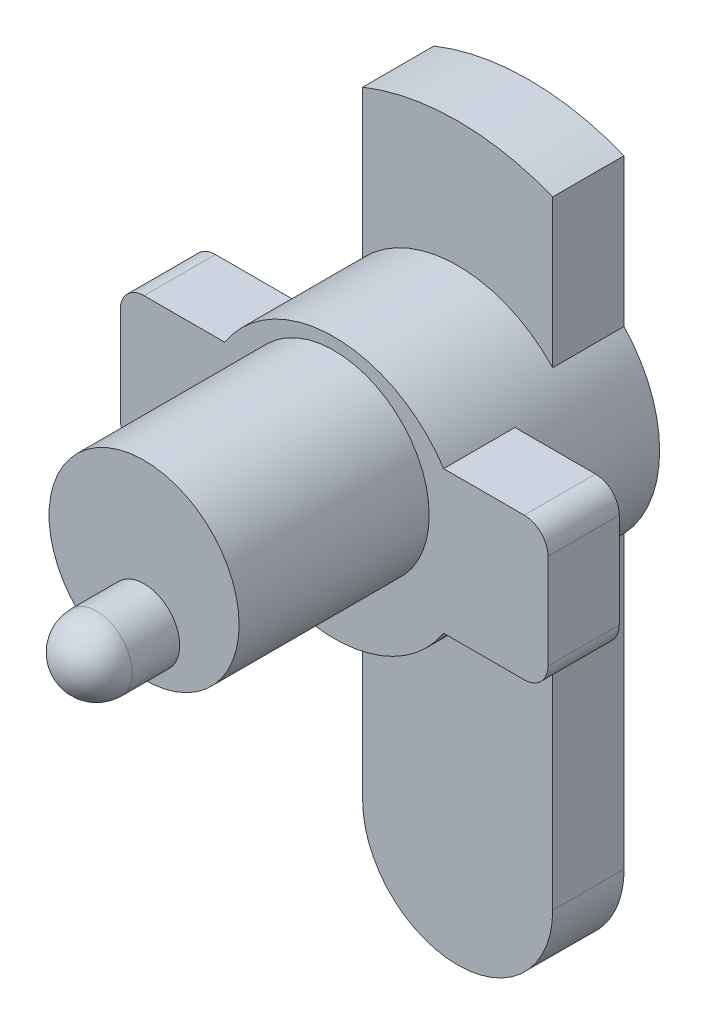
SolidWorks part; units mm, degrees
material "ABS PC"
ref_plane "Piano frontale" through (0, 0, 0) normal (0, 0, 1) x (1, 0, 0)
ref_plane "Piano superiore" through (0, 0, 0) normal (0, 1, 0) x (1, 0, 0)
ref_plane "Piano destro" through (0, 0, 0) normal (1, 0, 0) x (0, 0, -1)
sketch "Schizzo1" plane through (0, 0, 0) normal (0, 0, 1) x (1, 0, 0)
  circle A0 centre (0, 0) radius 2.75
  dimension "D1" = 5.5
extrude "Estrusione-Estrusione1" add sketch "Schizzo1" along normal blind 4.1
sketch "Schizzo2" plane through (0, 0, 4.1) normal (0, 0, 1) x (1, 0, 0)
  line L1 (-4.5, -1.5) -> (4.5, -1.5)
  line L2 (-4.5, -1.5) -> (-4.5, 1.5)
  line L3 (-4.5, 1.5) -> (4.5, 1.5)
  line L4 (4.5, -1.5) -> (4.5, 1.5)
  line L5 (-4.5, -1.5) -> (4.5, 1.5) construction
  line L6 (-4.5, 1.5) -> (4.5, -1.5) construction
  point P0 (0, 0)
  dimension "D1" = 9
  dimension "D2" = 3
extrude "Estrusione-Estrusione2" add sketch "Schizzo2" against normal blind 1.5
fillet "Raccordo1" radius 0.5 4 edges at (-4.5, -1.5, 3.35) (-4.5, 1.5, 3.35) (4.5, -1.5, 3.35) (4.5, 1.5, 3.35)
sketch "Schizzo3" plane through (0, 0, 4.1) normal (0, 0, 1) x (1, 0, 0)
  line L0 (0, 0) -> (0, 0.5) construction
  circle A0 centre (0, 0.5) radius 2
  arc A1 (2.3049, 1.5) -> (-2.3049, 1.5) centre (0, 0) ccw construction
  dimension "D1" = 4
  dimension "D2" = 0.5
extrude "Estrusione-Estrusione3" add sketch "Schizzo3" along normal blind 4
sketch "Schizzo4" plane through (0, 0, 8.1) normal (0, 0, 1) x (1, 0, 0)
  line L0 (0, -0.5) -> (0, 0) construction
  circle A0 centre (0, -0.5) radius 0.75
  circle A1 centre (0, 0.5) radius 2 construction
  dimension "D1" = 1.5
  dimension "D2" = 1
extrude "Estrusione-Estrusione4" add sketch "Schizzo4" along normal blind 1
sketch "Schizzo5" plane through (0, 0, 9.1) normal (0, 0, 1) x (1, 0, 0)
  line L0 (0, 0.25) -> (0, -1.25)
  circle A1 centre (0, -0.5) radius 0.75
  arc A2 (0, -1.25) -> (0, 0.25) centre (0, -0.5) ccw
  dimension "D1" = 0
revolve "Rivoluzione1" add sketch "Schizzo5" angle 180 about L0
sketch "Schizzo6" plane through (0, 0, 0) normal (0, 0, 1) x (1, 0, 0)
  line L0 (0, 0) -> (0, -2.75) construction
  line L2 (-2, -8) -> (-2, 5)
  line L4 (2, -8) -> (2, 5)
  line L5 (-2, -8) -> (2, 5) construction
  line L6 (-2, 5) -> (2, -8) construction
  arc A0 (-2, 5) -> (2, 5) centre (0, 0) cw
  circle A2 centre (0, 0) radius 2.75 construction
  arc A3 (2, -8) -> (-2, -8) centre (0, -8) cw
  point P0 (0, -1.5)
  dimension "D3" = 5
  dimension "D4" = 2
  dimension "D5" = 5.3852
  dimension "D1" = 4
  dimension "D2" = 13
extrude "Estrusione-Estrusione5" add sketch "Schizzo6" along normal blind 1.5
sketch "Schizzo7" plane through (0, 0, 0) normal (0, 0, -1) x (-1, 0, 0)
  circle A0 centre (0, 0.5) radius 1.5
  dimension "D1" = 3
extrude "Taglio-Estrusione2" cut sketch "Schizzo7" against normal offset from surface (3.1 mm away) 1 up to face at (2, 0.5, 4.1)
sketch "Schizzo8" plane through (0, 0, 3.1) normal (0, 0, -1) x (-1, 0, 0)
  circle A0 centre (0, 0.5) radius 0.5
  dimension "D1" = 1
extrude "Taglio-Estrusione5" cut sketch "Schizzo8" against normal offset from surface (4 mm away) 1 up to face at (0.75, -0.5, 8.1)
sketch "Schizzo9" plane through (0, 0, 0) normal (0, 0, -1) x (-1, 0, 0)
  line L0 (0, -9.5) -> (0, -1.5) construction
  line L3 (-0.5, -9.5) -> (-0.5, -1.5)
  line L4 (0.5, -9.5) -> (0.5, -1.5)
  arc A4 (-0.5, -9.5) -> (0.5, -9.5) centre (0, -9.5) ccw
  arc A5 (0.5, -1.5) -> (-0.5, -1.5) centre (0, -1.5) ccw
  arc A6 (-2, -8) -> (2, -8) centre (0, -8) ccw construction
  circle A7 centre (0, 0.5) radius 1.5 construction
  point P2 (0, -5.5)
  dimension "D1" = 1
extrude "Estrusione-Estrusione6" add sketch "Schizzo9" along normal blind 0.3
fillet "Raccordo5" radius 0.1 4 edges at (0.5, -5.5, -0.3) (0, -1, -0.3) (-0.5, -5.5, -0.3) (0, -10, -0.3)
